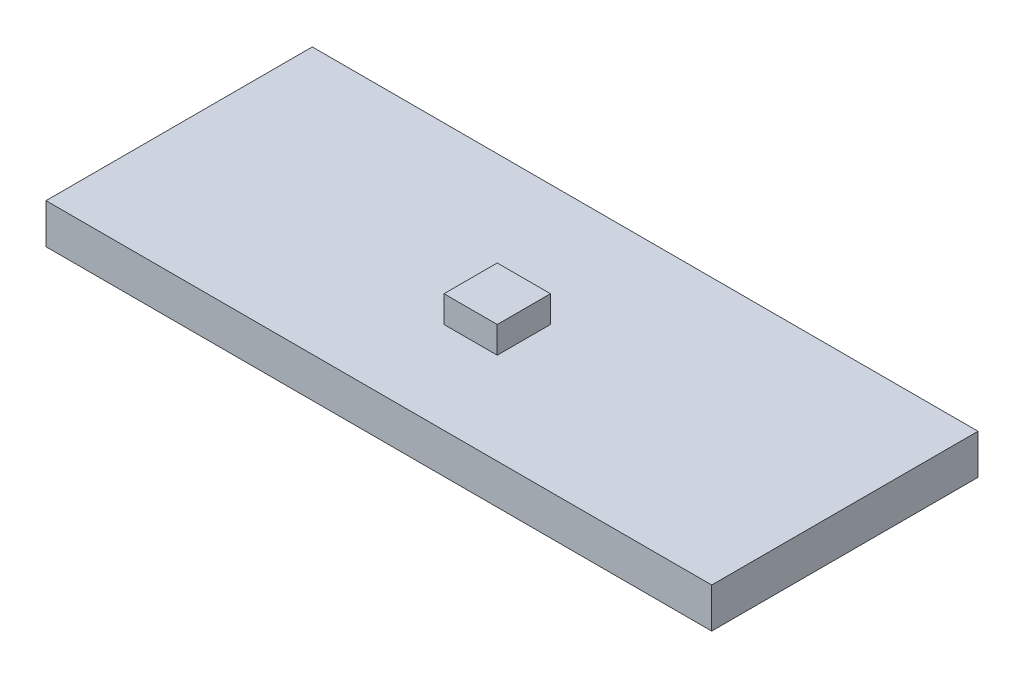
SolidWorks part; units mm, degrees
ref_plane "Front Plane" through (0, 0, 0) normal (0, 0, 1) x (1, 0, 0)
ref_plane "Top Plane" through (0, 0, 0) normal (0, 1, 0) x (1, 0, 0)
ref_plane "Right Plane" through (0, 0, 0) normal (1, 0, 0) x (0, 0, -1)
sketch "Sketch2" plane through (0, 0, 0) normal (0, 1, 0) x (1, 0, 0)
  line L1 (0, 0) -> (25, 0)
  line L2 (0, 0) -> (0, 10)
  line L3 (0, 10) -> (25, 10)
  line L4 (25, 0) -> (25, 10)
  dimension "D1" = 10
  dimension "D2" = 25
extrude "Boss-Extrude1" add sketch "Sketch2" along normal blind 1.5
sketch "Sketch3" plane through (0, 1.5, 0) normal (0, 1, 0) x (1, 0, 0)
  line L0 (0, 4.4453) -> (25, 4.4453) construction
  line L1 (0, 10) -> (0, 0) construction
  line L2 (25, 0) -> (25, 10) construction
  line L3 (12.5, 10) -> (12.5, 0) construction
  line L4 (25, 10) -> (0, 10) construction
  line L5 (0, 0) -> (25, 0) construction
  line L6 (12.5, 5.4453) -> (13.5, 5.4453)
  line L7 (13.5, 5.4453) -> (13.5, 3.4453)
  line L8 (13.5, 3.4453) -> (11.5, 3.4453)
  line L9 (11.5, 3.4453) -> (11.5, 5.4453)
  line L10 (11.5, 5.4453) -> (12.5, 5.4453)
  dimension "D1" = 1
  dimension "D2" = 2
  dimension "D3" = 2
extrude "Boss-Extrude2" add sketch "Sketch3" along normal blind 1
